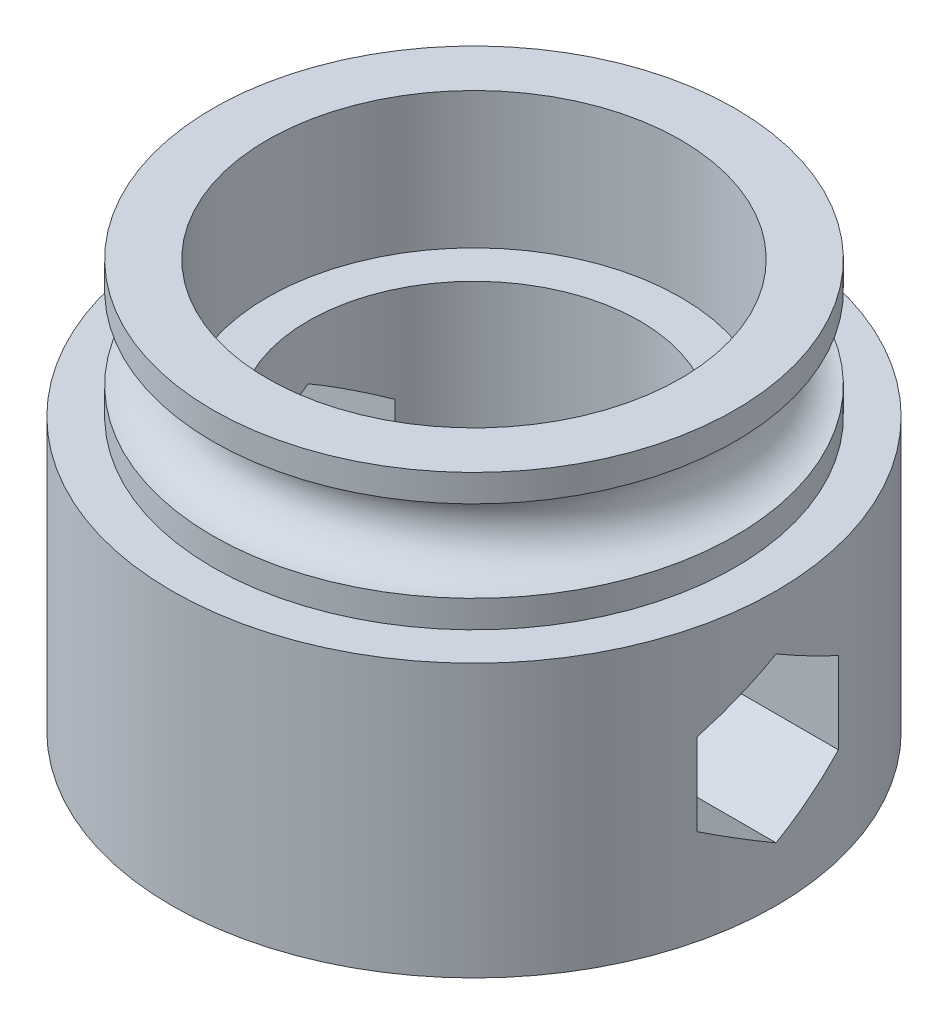
SolidWorks part; units mm, degrees
ref_plane "Front Plane" through (0, 0, 0) normal (0, 0, 1) x (1, 0, 0)
ref_plane "Top Plane" through (0, 0, 0) normal (0, 1, 0) x (1, 0, 0)
ref_plane "Right Plane" through (0, 0, 0) normal (1, 0, 0) x (0, 0, -1)
sketch "Sketch3" plane through (0, 0, 0) normal (0, 0, 1) x (1, 0, 0)
  line L0 (0, 0) -> (0, 1)
  line L1 (0, 1) -> (0.15, 1)
  line L2 (0.15, 1) -> (0.15, 1.5)
  line L3 (0.15, 1.5) -> (0.35, 1.5)
  line L4 (0.35, 1.5) -> (0.35, 1.4)
  line L5 (0.35, 1.1) -> (0.35, 1)
  line L6 (0.35, 1) -> (0.5, 1)
  line L7 (0.5, 1) -> (0.5, 0)
  line L8 (0.5, 0) -> (0, 0)
  line L9 (-0.6081, 0) -> (-0.6081, 0.5)
  arc A0 (0.35, 1.4) -> (0.35, 1.1) centre (0.35, 1.25) ccw
  dimension "D1" = 1.5
  dimension "D2" = 1
  dimension "D3" = 0.15
  dimension "D4" = 0.2
  dimension "D5" = 0.15
  dimension "D6" = 0.1
  dimension "D7" = 0.15
  dimension "D8" = 1
  dimension "D9" = 0.6081
  dimension "D10" = 0.5
revolve "Revolve1" add sketch "Sketch3" angle 360 about L9
sketch "Sketch11" plane through (0, 0, 0) normal (1, 0, 0) x (0, 0, -1)
  line L0 (0, 0) -> (0, 1) construction
  line L1 (0, 0.8) -> (-0.2598, 0.65)
  line L2 (-0.2598, 0.65) -> (-0.2598, 0.35)
  line L3 (-0.2598, 0.35) -> (0, 0.2)
  line L4 (0, 0.2) -> (0.2598, 0.35)
  line L5 (0.2598, 0.35) -> (0.2598, 0.65)
  line L6 (0.2598, 0.65) -> (0, 0.8)
  circle A0 centre (0, 0.5) radius 0.2598 construction
  point P10 (0, 0.5)
  dimension "D1" = 0.3
sketch "Sketch12" plane through (0, 0, 0) normal (1, 0, 0) x (0, 0, -1)
extrude "Cut-Extrude1" cut sketch "Sketch11" against normal through all both and the other way through all
